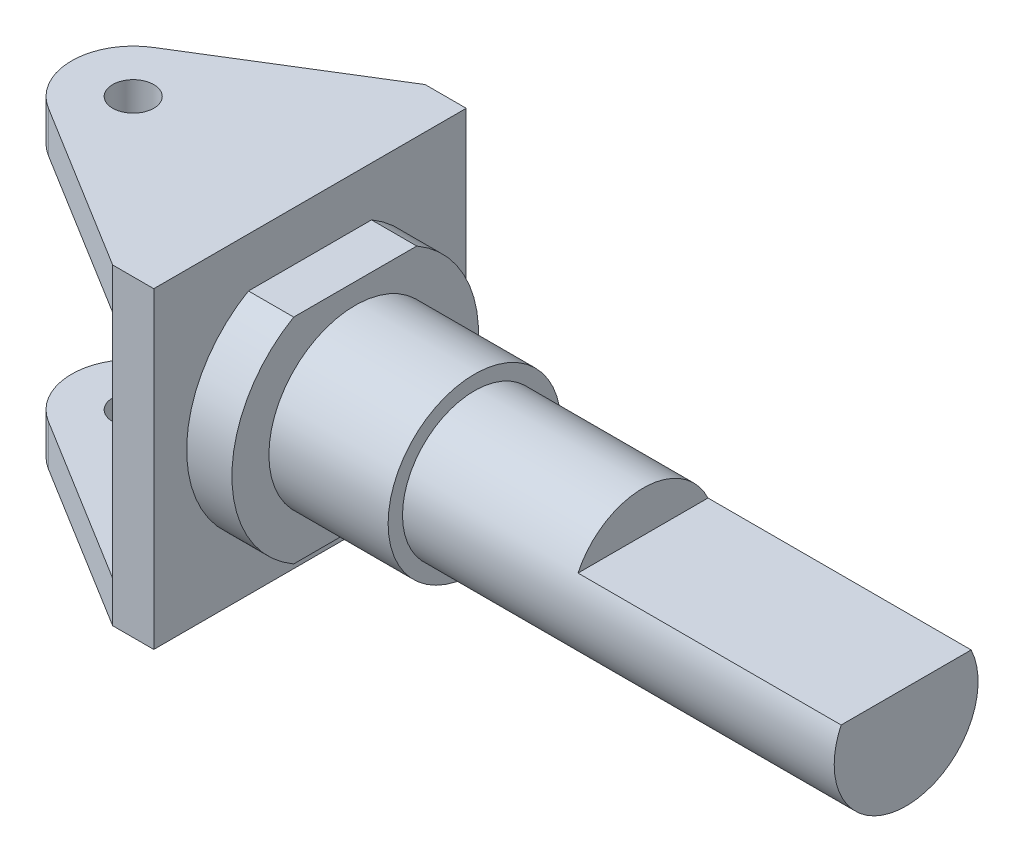
SolidWorks part; units mm, degrees
ref_plane "정면" through (0, 0, 0) normal (0, 0, 1) x (1, 0, 0)
ref_plane "윗면" through (0, 0, 0) normal (0, 1, 0) x (1, 0, 0)
ref_plane "우측면" through (0, 0, 0) normal (1, 0, 0) x (0, 0, -1)
sketch "스케치1" plane through (0, 0, 0) normal (0, 0, 1) x (1, 0, 0)
  line L0 (-16.6805, 0) -> (128.3195, 0) construction
  line L1 (-16.6805, 0) -> (-16.6805, 30)
  line L2 (-16.6805, 30) -> (-5.6805, 30)
  line L3 (-5.6805, 30) -> (-5.6805, 21)
  line L4 (-5.6805, 21) -> (23.3195, 21)
  line L5 (23.3195, 21) -> (23.3195, 17.5)
  line L6 (23.3195, 17.5) -> (128.3195, 17.5)
  line L7 (128.3195, 17.5) -> (128.3195, 0)
  line L8 (-16.6805, 0) -> (128.3195, 0)
  dimension "D1" = 60
  dimension "D2" = 35
  dimension "D3" = 145
  dimension "D4" = 105
  dimension "D5" = 29
  dimension "D6" = 42
revolve "회전1" add sketch "스케치1" angle 360 about L0
sketch "스케치2" plane through (128.3195, 0, 0) normal (1, 0, 0) x (0, 0, -1)
  line L1 (-18.6741, 19.2403) -> (34.9057, 19.2403)
  line L2 (-18.6741, 19.2403) -> (-18.6741, 7.5)
  line L3 (-18.6741, 7.5) -> (34.9057, 7.5)
  line L4 (34.9057, 19.2403) -> (34.9057, 7.5)
  circle A0 centre (0, 0) radius 17.5 construction
  dimension "D1" = 7.5
extrude "컷-돌출1" cut sketch "스케치2" against normal blind 64
sketch "스케치3" plane through (-5.6805, 0, 0) normal (1, 0, 0) x (0, 0, -1)
  line L1 (-29.1704, 37.0646) -> (28.416, 37.0646)
  line L2 (-29.1704, 37.0646) -> (-29.1704, 26)
  line L3 (-29.1704, 26) -> (28.416, 26)
  line L4 (28.416, 37.0646) -> (28.416, 26)
  line L9 (-25.4822, -26) -> (23.1352, -26)
  line L10 (-25.4822, -26) -> (-25.4822, -35.5558)
  line L11 (-25.4822, -35.5558) -> (23.1352, -35.5558)
  line L12 (23.1352, -26) -> (23.1352, -35.5558)
  circle A0 centre (0, 0) radius 21 construction
  dimension "D1" = 52
  dimension "D2" = 26
extrude "컷-돌출2" cut sketch "스케치3" against normal blind 64
sketch "스케치4" plane through (-16.6805, 0, 0) normal (-1, 0, 0) x (0, 0, 1)
  line L1 (-38, 38) -> (38, 38)
  line L2 (-38, 38) -> (-38, -38)
  line L3 (-38, -38) -> (38, -38)
  line L4 (38, 38) -> (38, -38)
  line L5 (-38, 38) -> (38, -38) construction
  line L6 (-38, -38) -> (38, 38) construction
  point P0 (0, 0)
  dimension "D1" = 76
  dimension "D2" = 76
extrude "보스-돌출1" add sketch "스케치4" along normal blind 10
sketch "스케치5" plane through (0, 38, 0) normal (0, 1, 0) x (1, 0, 0)
  line L0 (-26.6805, 38) -> (-67.56, 12.7638)
  line L2 (-26.6805, -38) -> (-67.56, -12.7638)
  arc A0 (-67.56, -12.7638) -> (-67.56, 12.7638) centre (-59.6805, 0) cw
  circle A1 centre (-59.6805, 0) radius 5
  line M3 (-26.6805, 38) -> (-26.6805, -38)
  dimension "D1" = 15
  dimension "D2" = 10
  dimension "D3" = 38
  dimension "D4" = 43
extrude "보스-돌출2" add sketch "스케치5" against normal blind 10 contours A0 L2 L0 A1 M3
mirror "대칭 복사1" about plane through (0, 0, 0) normal (0, 1, 0) of "보스-돌출2"
